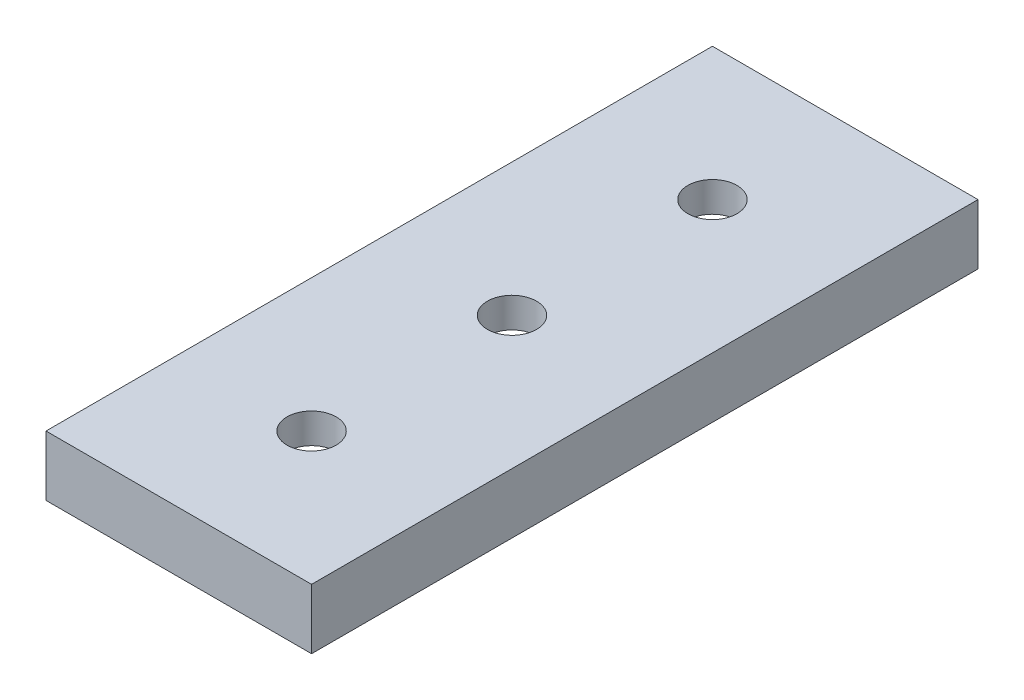
SolidWorks part; units mm, degrees
ref_plane "Front Plane" through (0, 0, 0) normal (0, 0, 1) x (1, 0, 0)
ref_plane "Top Plane" through (0, 0, 0) normal (0, 1, 0) x (1, 0, 0)
ref_plane "Right Plane" through (0, 0, 0) normal (1, 0, 0) x (0, 0, -1)
sketch "Sketch1" plane through (0, 0, 0) normal (0, 1, 0) x (1, 0, 0)
  line L1 (0, 0) -> (20.5, 0)
  line L2 (0, 0) -> (0, 60.5)
  line L3 (0, 60.5) -> (20.5, 60.5)
  line L4 (20.5, 0) -> (20.5, 60.5)
  circle A0 centre (10.25, 10.25) radius 2.45
  circle A1 centre (10.25, 50.25) radius 2.45
  circle A2 centre (10.25, 30.25) radius 2.45
  point P11 (0, 0)
  point P13 (10.25, 0)
  dimension "D3" = 4.9
  dimension "D4" = 4.9
  dimension "D5" = 4.9
  dimension "D1" = 60.5
  dimension "D2" = 20.5
  dimension "D6" = 20
  dimension "D7" = 20
  dimension "D8" = 10.25
extrude "Boss-Extrude1" add sketch "Sketch1" along normal blind 3
sketch "Sketch2" plane through (0, 3, 0) normal (0, 1, 0) x (1, 0, 0)
  line L1 (0, 0) -> (20.5, 0)
  line L2 (0, 0) -> (0, 60.5)
  line L3 (0, 60.5) -> (20.5, 60.5)
  line L4 (20.5, 0) -> (20.5, 60.5)
  line L5 (0, 0) -> (20.5, 60.5) construction
  line L6 (0, 60.5) -> (20.5, 0) construction
  line L7 (-3, -3) -> (23.5, -3)
  line L8 (-3, -3) -> (-3, 63.5)
  line L9 (-3, 63.5) -> (23.5, 63.5)
  line L10 (23.5, -3) -> (23.5, 63.5)
  line L11 (-3, -3) -> (23.5, 63.5) construction
  line L12 (-3, 63.5) -> (23.5, -3) construction
  point P0 (10.25, 30.25)
  point P7 (10.25, 30.25)
  dimension "D1" = 3
  dimension "D2" = 3
extrude "Boss-Extrude2" add sketch "Sketch2" against normal blind 6
